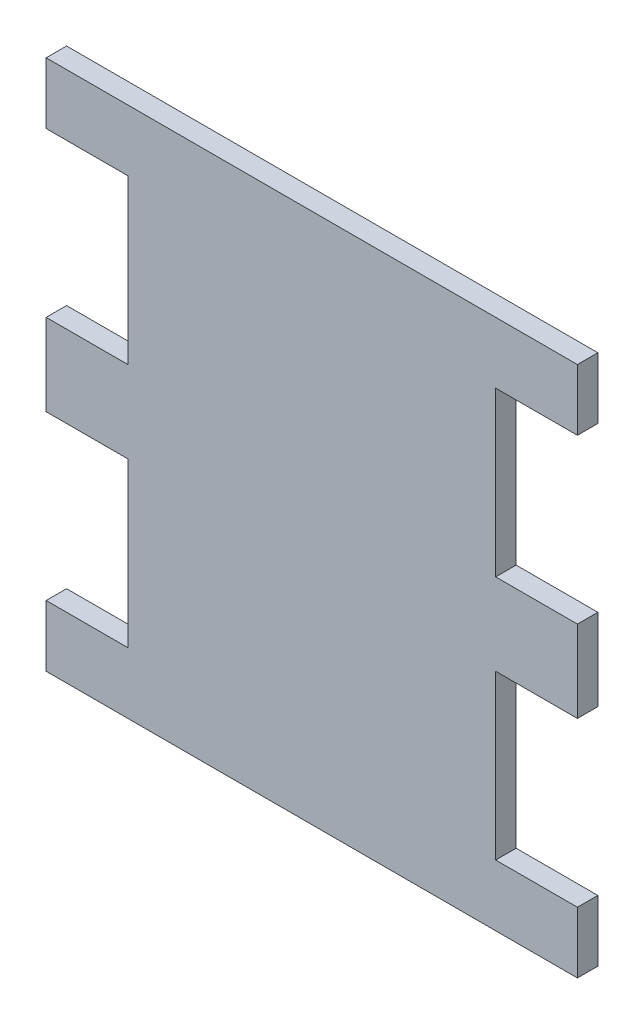
SolidWorks part; units mm, degrees
ref_plane "Plan de face" through (0, 0, 0) normal (0, 0, 1) x (1, 0, 0)
ref_plane "Plan de dessus" through (0, 0, 0) normal (0, 1, 0) x (1, 0, 0)
ref_plane "Plan de droite" through (0, 0, 0) normal (1, 0, 0) x (0, 0, -1)
sketch "Esquisse1" plane through (0, 0, 0) normal (0, 0, 1) x (1, 0, 0)
  line L1 (-33.4259, 41.5719) -> (96.5741, 41.5719)
  line L2 (-33.4259, 41.5719) -> (-33.4259, -88.4281)
  line L3 (-33.4259, -88.4281) -> (96.5741, -88.4281)
  line L4 (96.5741, 41.5719) -> (96.5741, -88.4281)
  dimension "D1" = 130
  dimension "D2" = 130
extrude "Boss.-Extru.1" add sketch "Esquisse1" along normal blind 5
sketch "Esquisse2" plane through (0, 0, 5) normal (0, 0, 1) x (1, 0, 0)
  line L0 (-33.4259, 41.5719) -> (-33.4259, -88.4281) construction
  line L1 (-33.4259, 26.5719) -> (-13.4259, 26.5719)
  line L2 (-33.4259, 26.5719) -> (-33.4259, -13.4281)
  line L3 (-33.4259, -13.4281) -> (-13.4259, -13.4281)
  line L4 (-13.4259, 26.5719) -> (-13.4259, -13.4281)
  line L5 (-33.4259, -88.4281) -> (96.5741, -88.4281) construction
  line L6 (-33.4259, -33.4281) -> (-13.4259, -33.4281)
  line L7 (-33.4259, -33.4281) -> (-33.4259, -73.4281)
  line L8 (-33.4259, -73.4281) -> (-13.4259, -73.4281)
  line L9 (-13.4259, -33.4281) -> (-13.4259, -73.4281)
  line L10 (96.5741, 41.5719) -> (-33.4259, 41.5719) construction
  dimension "D1" = 20
  dimension "D2" = 40
  dimension "D3" = 40
  dimension "D4" = 15
  dimension "D5" = 15
extrude "Enlèv. mat.-Extru.1" cut sketch "Esquisse2" against normal blind 10
sketch "Esquisse3" plane through (0, 0, 5) normal (0, 0, 1) x (1, 0, 0)
  line L0 (96.5741, -88.4281) -> (96.5741, 41.5719) construction
  line L1 (96.5741, 26.5719) -> (76.5741, 26.5719)
  line L2 (96.5741, 26.5719) -> (96.5741, -13.4281)
  line L3 (96.5741, -13.4281) -> (76.5741, -13.4281)
  line L4 (76.5741, 26.5719) -> (76.5741, -13.4281)
  line L5 (96.5741, 41.5719) -> (-33.4259, 41.5719) construction
  line L6 (-33.4259, -88.4281) -> (96.5741, -88.4281) construction
  line L7 (96.5741, -33.4281) -> (76.5741, -33.4281)
  line L8 (96.5741, -33.4281) -> (96.5741, -73.4281)
  line L9 (96.5741, -73.4281) -> (76.5741, -73.4281)
  line L10 (76.5741, -33.4281) -> (76.5741, -73.4281)
  dimension "D1" = 20
  dimension "D2" = 15
  dimension "D3" = 40
  dimension "D4" = 40
  dimension "D5" = 15
  dimension "D6" = 20
extrude "Enlèv. mat.-Extru.2" cut sketch "Esquisse3" against normal blind 10
